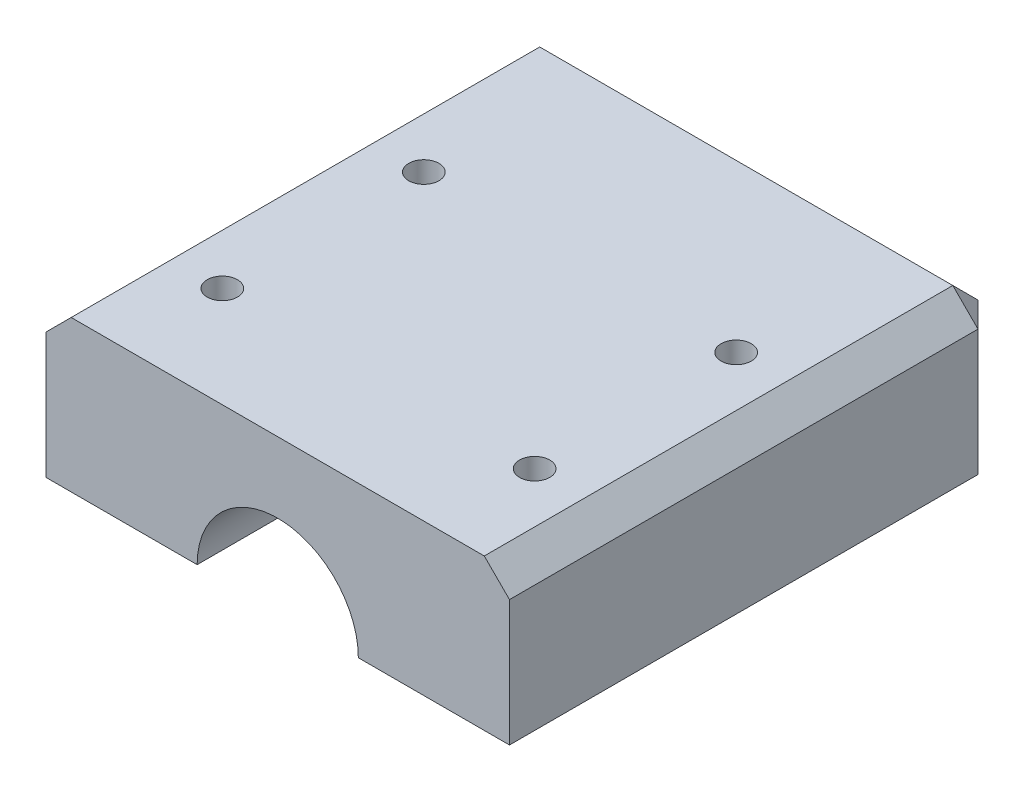
SolidWorks part; units mm, degrees
material "ABS"
ref_plane "Ön Düzlem" through (0, 0, 0) normal (0, 0, 1) x (1, 0, 0)
ref_plane "Üst Düzlem" through (0, 0, 0) normal (0, 1, 0) x (1, 0, 0)
ref_plane "Sağ Düzlem" through (0, 0, 0) normal (1, 0, 0) x (0, 0, -1)
sketch "Çizim1" plane through (0, 0, 0) normal (0, 0, 1) x (1, 0, 0)
  line L0 (-8, 0) -> (-23, 0)
  line L1 (-23, 0) -> (-23, 15)
  line L2 (-23, 15) -> (23, 15)
  line L3 (0, 15) -> (0, -22.4351) construction
  line L4 (23, 0) -> (23, 15)
  line L5 (8, 0) -> (23, 0)
  arc A0 (8, 0) -> (-8, 0) centre (0, 0) ccw
  dimension "D1" = 16
  dimension "D2" = 46
  dimension "D3" = 15
extrude "Yükseklik-Ekstrüzyon1" add sketch "Çizim1" against normal blind 45
sketch "Çizim2" plane through (0, 0, 0) normal (0, -1, 0) x (1, 0, 0)
  line L0 (-23, -45) -> (-23, 0) construction
  line L1 (23, -45) -> (-23, -45)
  line L2 (23, -45) -> (23, -40)
  line L3 (23, -40) -> (-23, -40)
  line L4 (-23, -45) -> (-23, -40)
  dimension "D1" = 5
extrude "Yükseklik-Ekstrüzyon2" add sketch "Çizim2" against normal blind 14
sketch "Çizim3" plane through (0, 0, -45) normal (0, 0, -1) x (-1, 0, 0)
  line L0 (23, 15) -> (23, 0) construction
  line L1 (-23, 15) -> (23, 15)
  line L2 (-23, 15) -> (-23, 4)
  line L3 (-18, 4) -> (18, 4)
  line L4 (23, 15) -> (23, 4)
  line L5 (-23, 4) -> (-23, 0)
  line L6 (-23, 0) -> (-18, 0)
  line L7 (23, 0) -> (-23, 0) construction
  line L8 (-18, 0) -> (-18, 4)
  line L9 (0, 0) -> (0, 15) construction
  line L10 (18, 0) -> (18, 4)
  line L11 (23, 0) -> (18, 0)
  line L12 (23, 4) -> (23, 0)
  dimension "D1" = 4
  dimension "D2" = 5
extrude "Yükseklik-Ekstrüzyon3" add sketch "Çizim3" along normal blind 4
chamfer "Pah1" distance 2.5 angle 45 5 edges at (-23, 15, -24.5) (-23, 7.5, -49) (23, 7.5, -49) (0, 15, -49) (23, 15, -24.5)
sketch "Çizim4" plane through (0, 0, 0) normal (0, -1, 0) x (1, 0, 0)
  line L0 (0, 0) -> (8, 0) construction
  line L1 (8, 0) -> (23, 0) construction
  line L2 (15.5, 0) -> (15.5, -49) construction
  line L3 (18, -49) -> (-18, -49) construction
  line L4 (0, 0) -> (0, -49) construction
  circle A0 centre (15.5, -10) radius 1.5
  circle A1 centre (15.5, -30) radius 1.5
  circle A2 centre (-15.5, -30) radius 1.5
  circle A3 centre (-15.5, -10) radius 1.5
  dimension "D1" = 3
  dimension "D2" = 3
  dimension "D3" = 10
  dimension "D4" = 20
extrude "Kes-Ekstrüzyon1" cut sketch "Çizim4" against normal blind 35
